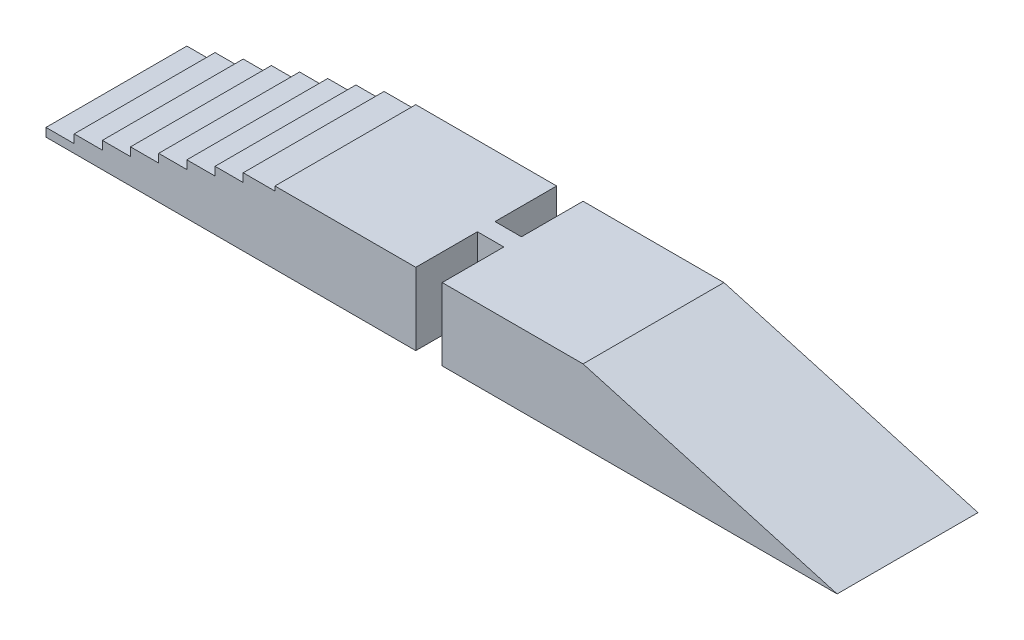
SolidWorks part; units mm, degrees
ref_plane "Front Plane" through (0, 0, 0) normal (0, 0, 1) x (1, 0, 0)
ref_plane "Top Plane" through (0, 0, 0) normal (0, 1, 0) x (1, 0, 0)
ref_plane "Right Plane" through (0, 0, 0) normal (1, 0, 0) x (0, 0, -1)
sketch "Sketch1" plane through (0, 0, 0) normal (0, 0, 1) x (1, 0, 0)
  line L0 (-1186.8985, 48.125) -> (-1026.8985, 48.125)
  line L1 (113.1015, 0) -> (913.1015, 0) construction
  line L2 (113.1015, 385) -> (113.1015, 410)
  line L3 (113.1015, 410) -> (913.1015, 410)
  line L4 (913.1015, 0) -> (913.1015, 410) construction
  line L5 (913.1015, 0) -> (1063.1015, 0) construction
  line L6 (913.1015, 0) -> (913.1015, 410) construction
  line L7 (913.1015, 410) -> (1063.1015, 410)
  line L8 (1063.1015, 0) -> (1063.1015, 410) construction
  line L9 (1063.1015, 0) -> (1863.1015, 0) construction
  line L10 (1063.1015, 0) -> (1063.1015, 410) construction
  line L11 (1063.1015, 410) -> (1863.1015, 410)
  line L12 (1863.1015, 0) -> (1863.1015, 410) construction
  line L14 (-1186.8985, 48.125) -> (-1186.8985, 0)
  line L15 (-1186.8985, 0) -> (113.1015, 0) construction
  line L17 (-1026.8985, 96.25) -> (-866.8985, 96.25)
  line L18 (-866.8985, 144.375) -> (-706.8985, 144.375)
  line L19 (-706.8985, 192.5) -> (-546.8985, 192.5)
  line L20 (-546.8985, 240.625) -> (-386.8985, 240.625)
  line L21 (-386.8985, 288.75) -> (-226.8985, 288.75)
  line L22 (-226.8985, 336.875) -> (-66.8985, 336.875)
  line L23 (-66.8985, 385) -> (113.1015, 385)
  line L24 (-1026.8985, 96.25) -> (-1026.8985, 48.125)
  line L25 (-866.8985, 144.375) -> (-866.8985, 96.25)
  line L26 (-706.8985, 192.5) -> (-706.8985, 144.375)
  line L27 (-546.8985, 240.625) -> (-546.8985, 192.5)
  line L28 (-386.8985, 288.75) -> (-386.8985, 240.625)
  line L29 (-226.8985, 336.875) -> (-226.8985, 288.75)
  line L30 (-66.8985, 385) -> (-66.8985, 336.875)
  line L31 (-1186.8985, 0) -> (3305.9805, 0)
  line L34 (1863.1015, 0) -> (3995.8021, 0) construction
  line L35 (1863.1015, 410) -> (3305.9805, 0)
  line L36 (-1186.8985, 410) -> (-1186.8985, 0) construction
  line L37 (-1186.8985, 48.125) -> (113.1015, 48.125) construction
  line L38 (-1026.8985, 410) -> (-1026.8985, 0) construction
  line L39 (-1186.8985, 96.25) -> (113.1015, 96.25) construction
  line L40 (-866.8985, 410) -> (-866.8985, 0) construction
  line L41 (-1186.8985, 144.375) -> (113.1015, 144.375) construction
  line L42 (-706.8985, 410) -> (-706.8985, 0) construction
  line L43 (-1186.8985, 192.5) -> (113.1015, 192.5) construction
  line L44 (-546.8985, 410) -> (-546.8985, 0) construction
  line L45 (-1186.8985, 240.625) -> (113.1015, 240.625) construction
  line L46 (-386.8985, 410) -> (-386.8985, 0) construction
  line L47 (-1186.8985, 288.75) -> (113.1015, 288.75) construction
  line L48 (-226.8985, 410) -> (-226.8985, 0) construction
  line L49 (-1186.8985, 336.875) -> (113.1015, 336.875) construction
  line L50 (-66.8985, 410) -> (-66.8985, 0) construction
  line L51 (-1186.8985, 385) -> (113.1015, 385) construction
  circle A0 centre (1863.1015, 410) radius 1500 construction
  point P9 (0, 0)
  dimension "D1" = 150
  dimension "D2" = 800
  dimension "D3" = 800
  dimension "D4" = 410
  dimension "D5" = 1500
  dimension "D6" = 1300
  dimension "D7" = 160
  dimension "D8" = 180
  dimension "D9" = 160
  dimension "D10" = 160
  dimension "D11" = 160
  dimension "D12" = 160
  dimension "D13" = 160
  dimension "D14" = 160
  dimension "D15" = 48.125
  dimension "D16" = 25
extrude "Boss-Extrude1" add sketch "Sketch1" along normal blind 800
sketch "Sketch3" plane through (0, 410, 0) normal (0, 1, 0) x (1, 0, 0)
  line L0 (913.1015, 0) -> (913.1015, -800) construction
  line L1 (1863.1015, -800) -> (113.1015, -800) construction
  line L2 (1074.0954, 0) -> (1063.1015, 0)
  line L3 (1063.1015, 0) -> (1863.1015, 0) construction
  line L4 (1063.1015, 0) -> (1063.1015, -800) construction
  line L6 (913.1015, -800) -> (1063.1015, -800)
  line L7 (913.1015, -350) -> (1063.1015, -350) construction
  line L8 (913.1015, -800) -> (913.1015, -450)
  line L13 (913.1015, -350) -> (1063.1015, -350)
  line L14 (913.1015, -350) -> (913.1015, 0)
  line L15 (913.1015, 0) -> (1063.1015, 0)
  line L16 (1063.1015, -350) -> (1063.1015, 0)
  line L17 (913.1015, -450) -> (1063.1015, -450)
  line L18 (1063.1015, -800) -> (1063.1015, -450)
  line M17 (1863.1015, 0) -> (113.1015, 0)
  line M19 (113.1015, -800) -> (1863.1015, -800)
  dimension "D1" = 350
  dimension "D2" = 350
extrude "Cut-Extrude1" cut sketch "Sketch3" against normal blind 800 contours L13 L16 L14 M17 | L18 L17 L8 M19
